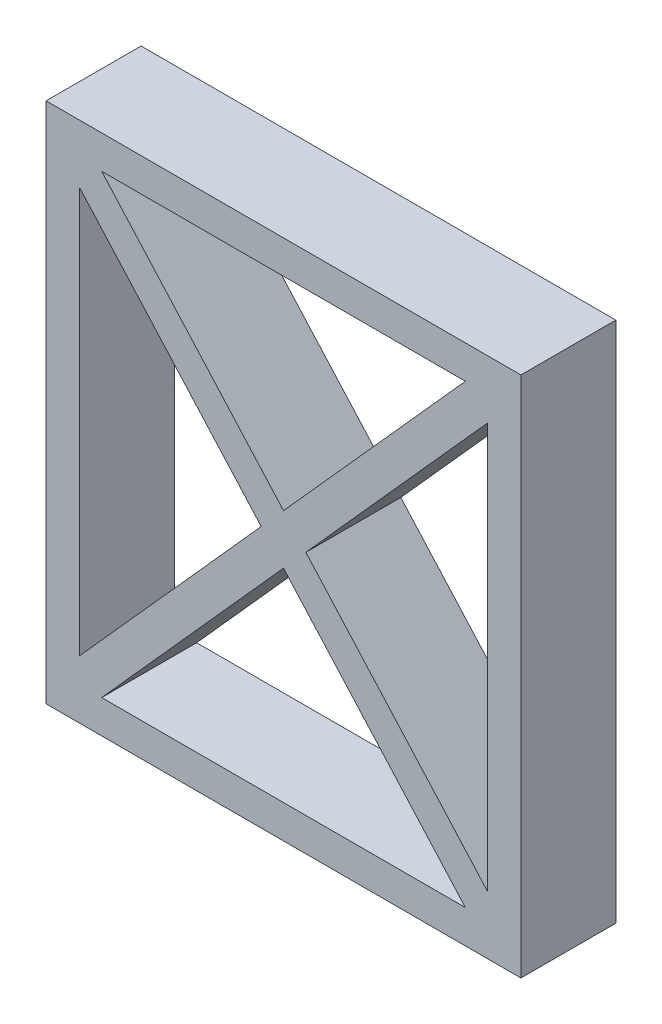
SolidWorks part; units mm, degrees
ref_plane "Front" through (0, 0, 0) normal (0, 0, 1) x (1, 0, 0)
ref_plane "Top" through (0, 0, 0) normal (0, 1, 0) x (1, 0, 0)
ref_plane "Right" through (0, 0, 0) normal (1, 0, 0) x (0, 0, -1)
sketch "Skizze1" plane through (0, 0, 0) normal (0, 0, 1) x (1, 0, 0)
  line L0 (-50, 0) -> (50, 0)
  line L5 (50, 0) -> (50, -110)
  line L6 (50, 236.0027) -> (50, -163.9973) construction
  line L7 (50, -110) -> (-50, -110)
  line L8 (-50, 236.0027) -> (-50, -163.9973) construction
  line L9 (-50, -110) -> (-50, 0)
  line L11 (-43, -12.2454) -> (-43, -97.7546)
  line L12 (-38.301, -103) -> (38.301, -103)
  line L13 (43, -97.7546) -> (43, -12.2454)
  line L14 (38.301, -7) -> (-38.301, -7)
  line L15 (-43, -7) -> (43, -103) construction
  line L16 (43, -7) -> (-43, -103) construction
  line L17 (-38.301, -7) -> (0, -49.7546)
  line L18 (-43, -12.2454) -> (-4.699, -55)
  line L19 (43, -12.2454) -> (4.699, -55)
  line L20 (38.301, -7) -> (0, -49.7546)
  line L21 (-4.699, -55) -> (-43, -97.7546)
  line L22 (4.699, -55) -> (43, -97.7546)
  line L23 (0, -60.2454) -> (-38.301, -103)
  line L24 (0, -60.2454) -> (38.301, -103)
  point P0 (0, 0)
  dimension "D1" = 110
  dimension "D2" = 7
  dimension "D3" = 7
  dimension "D4" = 7
  dimension "D5" = 7
  dimension "D6" = 3.5
  dimension "D7" = 3.5
  dimension "D8" = 3.5
  dimension "D9" = 3.5
extrude "Aufsatz-Linear austragen1" add sketch "Skizze1" along normal blind 20
